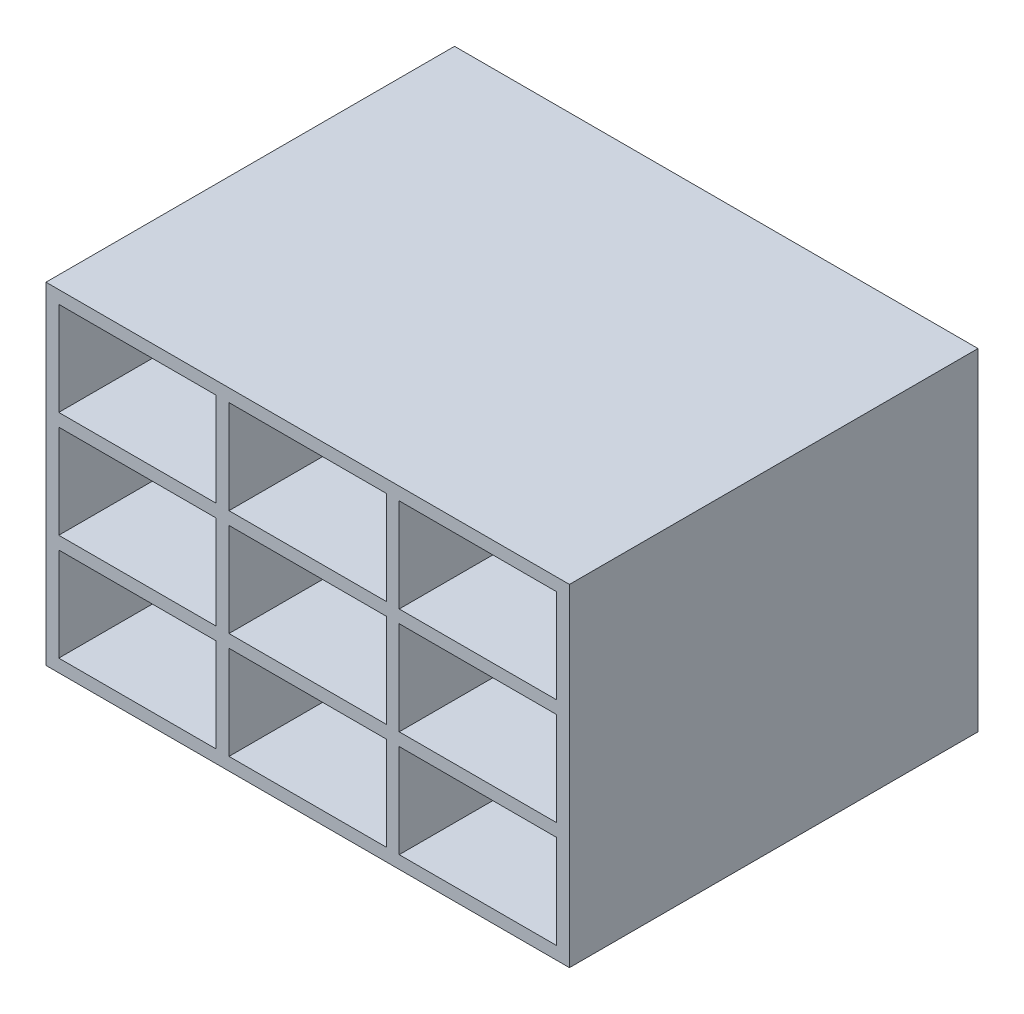
SolidWorks part; units mm, degrees
ref_plane "Alzado" through (0, 0, 0) normal (0, 0, 1) x (1, 0, 0)
ref_plane "Planta" through (0, 0, 0) normal (0, 1, 0) x (1, 0, 0)
ref_plane "Vista lateral" through (0, 0, 0) normal (1, 0, 0) x (0, 0, -1)
sketch "Croquis1" plane through (0, 0, 0) normal (0, 0, 1) x (1, 0, 0)
  line L5 (0, 0) -> (0, 83.3333) construction
  line L6 (0, 83.3333) -> (0, 166.6667) construction
  line L9 (0, 166.6667) -> (0, 250) construction
  line L10 (0, 250) -> (133.3333, 250) construction
  line L11 (133.3333, 250) -> (266.6667, 250) construction
  line L12 (266.6667, 250) -> (400, 250) construction
  line L13 (0, 0) -> (400, 0) construction
  line L14 (400, 0) -> (400, 250) construction
  line L15 (0, 166.6667) -> (400, 166.6667) construction
  line L16 (0, 83.3333) -> (400, 83.3333) construction
  line L17 (133.3333, 250) -> (133.3333, 0) construction
  line L18 (266.6667, 250) -> (266.6667, 0) construction
  line L19 (128.3333, 250) -> (128.3333, 0)
  line L20 (5, 166.6667) -> (5, 245)
  line L21 (5, 245) -> (133.3333, 245)
  line L22 (-5, 161.6667) -> (400, 161.6667)
  line L23 (261.6667, 250) -> (261.6667, 0)
  line L24 (133.3333, 245) -> (266.6667, 245)
  line L25 (266.6667, 245) -> (395, 245)
  line L26 (395, 5) -> (395, 245)
  line L27 (5, 5) -> (395, 5)
  line L28 (5, 5) -> (5, 83.3333)
  line L29 (-5, 78.3333) -> (400, 78.3333)
  line L30 (5, 83.3333) -> (5, 166.6667)
  line L31 (138.3333, 250) -> (138.3333, 0)
  line L32 (-5, 166.6667) -> (-5, 255)
  line L33 (-5, 255) -> (133.3333, 255)
  line L34 (-5, 171.6667) -> (400, 171.6667)
  line L35 (271.6667, 250) -> (271.6667, 0)
  line L36 (133.3333, 255) -> (266.6667, 255)
  line L37 (266.6667, 255) -> (405, 255)
  line L38 (405, -5) -> (405, 255)
  line L39 (-5, -5) -> (405, -5)
  line L40 (-5, -5) -> (-5, 83.3333)
  line L41 (-5, 88.3333) -> (400, 88.3333)
  line L42 (-5, 83.3333) -> (-5, 166.6667)
  line L43 (0, 161.6667) -> (400, 161.6667) construction
  line L44 (0, 171.6667) -> (400, 171.6667) construction
  line L45 (0, 88.3333) -> (400, 88.3333) construction
  line L46 (0, 78.3333) -> (400, 78.3333) construction
  dimension "D1" = 5
  dimension "D2" = 5
  dimension "D3" = 400
  dimension "D4" = 250
extrude "Saliente-Extruir3" add sketch "Croquis1" against normal blind 300
sketch "Croquis4" plane through (0, 0, -300) normal (0, 0, -1) x (-1, 0, 0)
  line L4 (5, -5) -> (5, 255)
  line L5 (5, 255) -> (-405, 255)
  line L6 (-405, 255) -> (-405, -5)
  line L7 (-405, -5) -> (5, -5)
  line L8 (5, -5) -> (5, 255)
  line L9 (5, 255) -> (-405, 255)
  line L10 (-405, 255) -> (-405, -5)
  line L11 (-405, -5) -> (5, -5)
  dimension "D1" = 0
extrude "Saliente-Extruir4" add sketch "Croquis4" along normal blind 20
